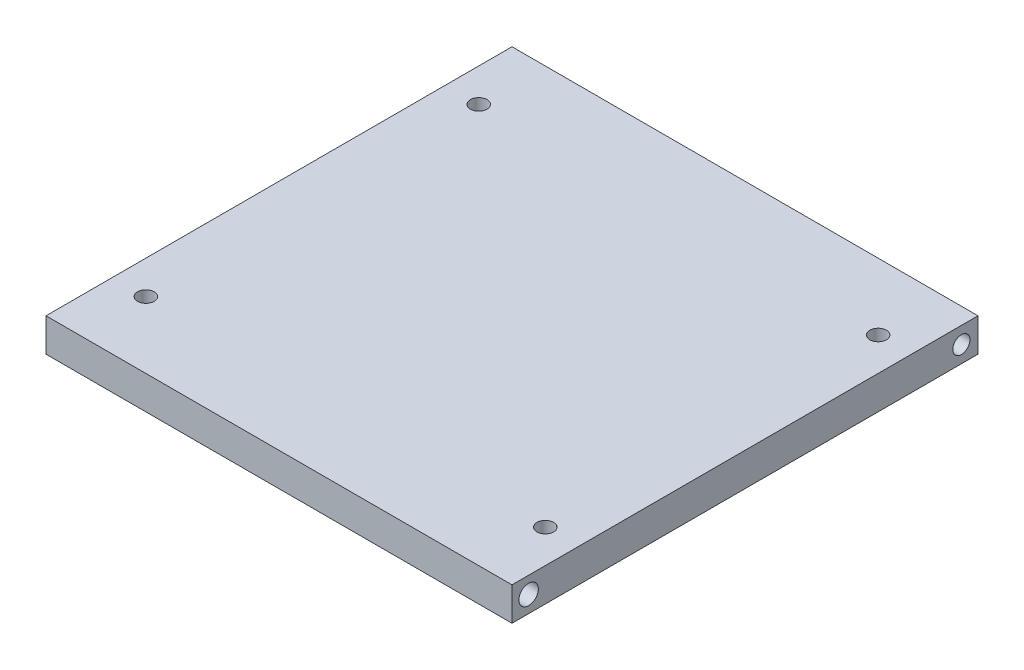
SolidWorks part; units mm, degrees
ref_plane "Front Plane" through (0, 0, 0) normal (0, 0, 1) x (1, 0, 0)
ref_plane "Top Plane" through (0, 0, 0) normal (0, 1, 0) x (1, 0, 0)
ref_plane "Right Plane" through (0, 0, 0) normal (1, 0, 0) x (0, 0, -1)
sketch "Sketch1" plane through (0, 0, 0) normal (0, 1, 0) x (1, 0, 0)
  line L1 (0, 0) -> (84, 0)
  line L2 (0, 0) -> (0, 84)
  line L3 (0, 84) -> (84, 84)
  line L4 (84, 0) -> (84, 84)
  dimension "D1" = 84
  dimension "D2" = 84
extrude "Boss-Extrude1" add sketch "Sketch1" along normal blind 6
sketch "Sketch2" plane through (0, 6, 0) normal (0, 1, 0) x (1, 0, 0)
  line L0 (84, 84) -> (0, 84) construction
  line L1 (0, 84) -> (0, 0) construction
  circle A0 centre (6, 72) radius 1.5
  dimension "D1" = 3
  dimension "D3" = 6
  dimension "D2" = 12
extrude "Cut-Extrude1" cut sketch "Sketch2" against normal blind 6
pattern_linear "LPattern1" count 2 spacing 72 along (1, 0, 0) count 2 spacing 60 along (0, 0, 1) of "Cut-Extrude1"
sketch "Sketch3" plane through (0, 0, 0) normal (-1, 0, 0) x (0, 0, 1)
  line L0 (-84, 3) -> (-3, 3) construction
  line L1 (-84, 6) -> (-84, 0) construction
  line L2 (0, 6) -> (0, 0) construction
  circle A0 centre (-81, 3) radius 1.5499
  circle A1 centre (-3, 3) radius 1.7482
  dimension "D1" = 3
  dimension "D2" = 3
extrude "Cut-Extrude2" cut sketch "Sketch3" against normal blind 10
ref_plane "Plane1" through (42, 0, 0) normal (-1, 0, 0) x (0, 0, 1)
mirror "Mirror1" about plane through (42, 0, 0) normal (-1, 0, 0) of "Cut-Extrude2"
